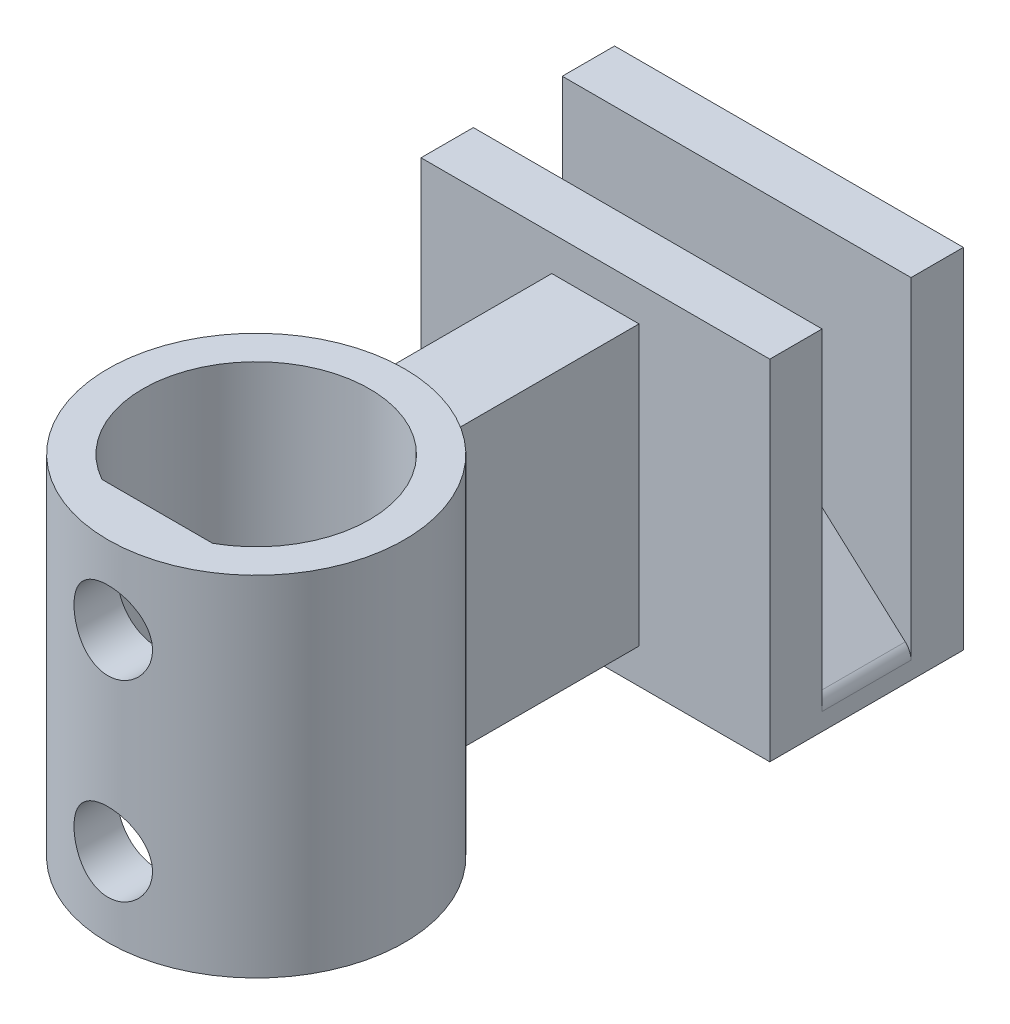
SolidWorks part; units mm, degrees
ref_plane "Front Plane" through (0, 0, 0) normal (0, 0, 1) x (1, 0, 0)
ref_plane "Top Plane" through (0, 0, 0) normal (0, 1, 0) x (1, 0, 0)
ref_plane "Right Plane" through (0, 0, 0) normal (1, 0, 0) x (0, 0, -1)
sketch "Sketch2" plane through (0, 0, 0) normal (0, 0, 1) x (1, 0, 0)
  line L1 (-10, -5) -> (10, -5)
  line L2 (-10, -5) -> (-10, 5)
  line L3 (-10, 5) -> (10, 5)
  line L4 (10, -5) -> (10, 5)
  line L5 (-10, -5) -> (10, 5) construction
  line L6 (-10, 5) -> (10, -5) construction
  point P0 (0, 0)
  dimension "D1" = 10
  dimension "D2" = 20
extrude "Boss-Extrude1" add sketch "Sketch2" along normal mid plane 5.1
chamfer "Chamfer1" distance 9.5 angle 42 2 edges at (10, 5, 0) (-10, 5, 0)
fillet "Fillet3" radius 1 4 edges at (-10, -3.5538, 0) (10, -3.5538, 0) (0.5, 5, 0) (-0.5, 5, 0)
sketch "Sketch3" plane through (0, 0, 2.55) normal (0, 0, 1) x (1, 0, 0)
  line L0 (-10, -5) -> (10, -5) construction
  line L1 (-10, 15) -> (10, 15)
  line L2 (-10, 15) -> (-10, -5)
  line L3 (-10, -5) -> (10, -5)
  line L4 (10, 15) -> (10, -5)
  line L5 (-10, 15) -> (10, -5) construction
  line L6 (-10, -5) -> (10, 15) construction
  point P0 (0, 5)
  dimension "D1" = 20
  dimension "D2" = 20
extrude "Boss-Extrude2" add sketch "Sketch3" along normal blind 3
mirror "Mirror1" about plane through (0, 0, 0) normal (0, 0, 1) of "Boss-Extrude2"
sketch "Sketch6" plane through (0, 0, 0) normal (0, 1, 0) x (1, 0, 0)
  line L0 (-3.175, -30.6718) -> (3.175, -30.6718)
  arc A0 (3.175, -30.6718) -> (-3.175, -30.6718) centre (0, -25) ccw
  circle A1 centre (0, -25) radius 8.5
  dimension "D1" = 13
  dimension "D2" = 2
  dimension "D3" = 25
  dimension "D4" = 6.35
extrude "Boss-Extrude3" add sketch "Sketch6" along normal up to surface and the other way up to surface separate body up to face at (0, 15, 4.05) other way up to face at (0, -5, 0)
sketch "Sketch5" plane through (0, 0, 5.55) normal (0, 0, 1) x (1, 0, 0)
  line L0 (-10, -5) -> (10, -5) construction
  line L1 (-2.5, 13) -> (2.5, 13)
  line L2 (-2.5, 13) -> (-2.5, -3)
  line L3 (-2.5, -3) -> (2.5, -3)
  line L4 (2.5, 13) -> (2.5, -3)
  line L5 (-2.5, 13) -> (2.5, -3) construction
  line L6 (-2.5, -3) -> (2.5, 13) construction
  line L7 (10, 15) -> (-10, 15) construction
  point P0 (0, 5)
  dimension "D1" = 2
  dimension "D2" = 2
  dimension "D3" = 5
extrude "Boss-Extrude4" add sketch "Sketch5" along normal up to surface (11.326 mm away)
ref_plane "Plane1" through (0, 0, 20) normal (0, 0, 1) x (1, 0, 0)
sketch "Sketch7" plane through (0, 0, 20) normal (0, 0, 1) x (1, 0, 0)
  line L0 (-8.5, -5) -> (8.5, -5) construction
  line L1 (6.5, 15) -> (-6.5, 15) construction
  circle A0 centre (0, 10.5) radius 2.25
  circle A1 centre (0, -0.5) radius 2.25
  dimension "D1" = 4.5
  dimension "D2" = 4.5
  dimension "D3" = 4.5
  dimension "D4" = 4.5
extrude "Cut-Extrude1" cut sketch "Sketch7" along normal up to surface (13.1968 mm away)
